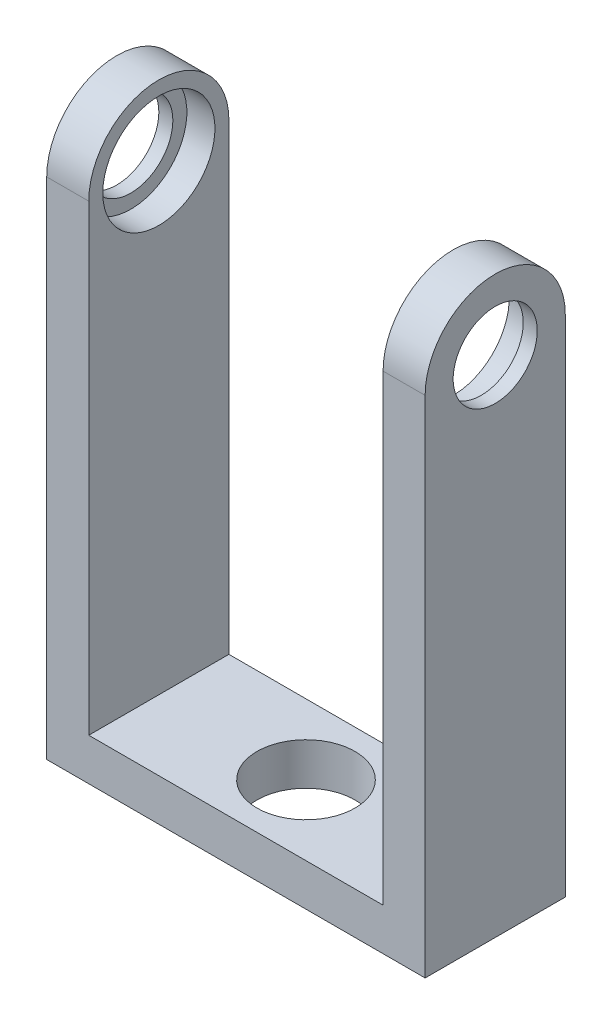
SolidWorks part; units mm, degrees
ref_plane "Front Plane" through (0, 0, 0) normal (0, 0, 1) x (1, 0, 0)
ref_plane "Top Plane" through (0, 0, 0) normal (0, 1, 0) x (1, 0, 0)
ref_plane "Right Plane" through (0, 0, 0) normal (1, 0, 0) x (0, 0, -1)
sketch "Sketch1" plane through (0, 0, 0) normal (0, 1, 0) x (1, 0, 0)
  line L1 (-13.5, -5) -> (13.5, -5)
  line L2 (-13.5, -5) -> (-13.5, 5)
  line L3 (-13.5, 5) -> (13.5, 5)
  line L4 (13.5, -5) -> (13.5, 5)
  line L5 (0, 5) -> (0, -5) construction
  line L6 (-13.5, 0) -> (13.5, 0) construction
  point P1 (0, 0)
  dimension "D1" = 10
  dimension "D2" = 27
extrude "Boss-Extrude1" add sketch "Sketch1" along normal blind 3
sketch "Sketch3" plane through (0, 0, 0) normal (1, 0, 0) x (0, 0, -1)
  line L0 (0, 0) -> (0, 16.3575) construction
sketch3d "3DSketch1" plane through (0, 0, 0) normal (0, 0, 1) x (1, 0, 0)
  dimension "D1" = 13.5
sketch "Sketch5" plane through (13.5, 0, 0) normal (1, 0, 0) x (0, 0, -1)
  line L0 (5.5, 0) -> (-5.5, 0) construction
  line L1 (-5, 3) -> (5, 3)
  line L2 (-5, 3) -> (-5, 36)
  line L4 (5, 3) -> (5, 36)
  arc A0 (-5, 36) -> (5, 36) centre (0, 36) cw
  circle A1 centre (0, 36) radius 3
  dimension "D2" = 6
  dimension "D1" = 36
extrude "Boss-Extrude3" add sketch "Sketch5" against normal blind 3
sketch "Sketch6" plane through (0, 3, 0) normal (0, 1, 0) x (1, 0, 0)
  circle A0 centre (0, 0) radius 1.5
  dimension "D1" = 3
extrude "Cut-Extrude1" cut sketch "Sketch6" against normal blind 3
sketch "Sketch7" plane through (10.5, 0, 0) normal (-1, 0, 0) x (0, 0, 1)
  circle A0 centre (0, 36) radius 4
  dimension "D1" = 8
extrude "Cut-Extrude2" cut sketch "Sketch7" against normal blind 2
mirror "Mirror3" about plane through (0, 0, 0) normal (1, 0, 0) of "Cut-Extrude2", "Boss-Extrude3", "Boss-Extrude1"
sketch "Sketch8" plane through (0, 3, 0) normal (0, 1, 0) x (1, 0, 0)
  circle A0 centre (0, 0) radius 3.5
  dimension "D1" = 7
extrude "Cut-Extrude4" cut sketch "Sketch8" against normal through all
